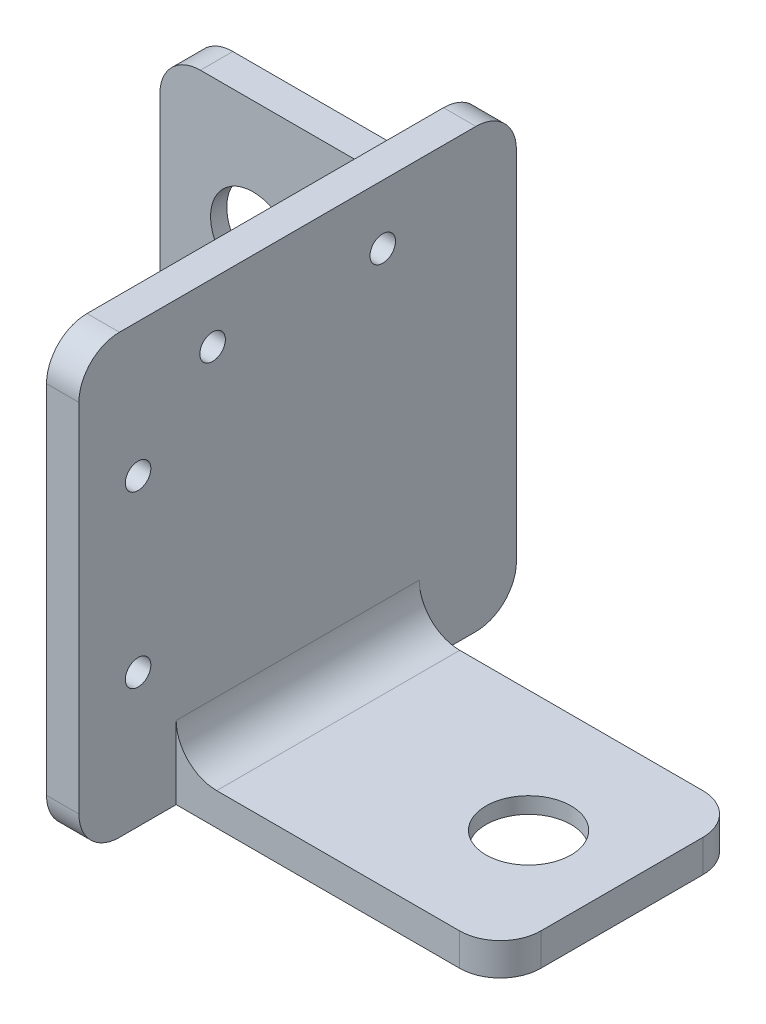
SolidWorks part; units mm, degrees
material "Du"
ref_plane "Front Plane" through (0, 0, 0) normal (0, 0, 1) x (1, 0, 0)
ref_plane "Top Plane" through (0, 0, 0) normal (0, 1, 0) x (1, 0, 0)
ref_plane "Right Plane" through (0, 0, 0) normal (1, 0, 0) x (0, 0, -1)
sketch "Sketch1" plane through (0, 0, 0) normal (1, 0, 0) x (0, 0, -1)
  line L1 (-27, -27) -> (27, -27)
  line L2 (-27, -27) -> (-27, 27)
  line L3 (-27, 27) -> (27, 27)
  line L4 (27, -27) -> (27, 27)
  line L5 (-27, -27) -> (27, 27) construction
  line L6 (-27, 27) -> (27, -27) construction
  point P0 (0, 0)
  dimension "D1" = 54
  dimension "D2" = 54
extrude "Boss-Extrude1" add sketch "Sketch1" along normal blind 4
fillet "Fillet1" radius 5 4 edges at (2, -27, 27) (2, -27, -27) (2, 27, -27) (2, 27, 27)
sketch "Sketch2" plane through (4, 0, 0) normal (1, 0, 0) x (0, 0, -1)
  line L0 (-22, -27) -> (22, -27) construction
  line L1 (-14.9965, -27) -> (15.0035, -27)
  line L2 (-14.9965, -27) -> (-14.9965, -23)
  line L3 (-14.9965, -23) -> (15.0035, -23)
  line L4 (15.0035, -27) -> (15.0035, -23)
  dimension "D1" = 30
  dimension "D2" = 4
extrude "Boss-Extrude2" add sketch "Sketch2" along normal blind 3
sketch "Sketch3" plane through (7, 0, 0) normal (1, 0, 0) x (0, 0, -1)
  line L1 (-14.9965, -27) -> (15.0035, -27)
  line L2 (-14.9965, -27) -> (-14.9965, -23)
  line L3 (-14.9965, -23) -> (15.0035, -23)
  line L4 (15.0035, -27) -> (15.0035, -23)
  dimension "D1" = 30
  dimension "D2" = 4
extrude "Boss-Extrude3" add sketch "Sketch3" along normal blind 37
sketch "Sketch4" plane through (0, 0, 0) normal (-1, 0, 0) x (0, 0, 1)
  line L0 (-27, -22) -> (-27, 22) construction
  line L1 (-27, 15.0038) -> (-23, 15.0038)
  line L2 (-27, 15.0038) -> (-27, -14.9964)
  line L3 (-27, -14.9964) -> (-23, -14.9964)
  line L4 (-23, 15.0038) -> (-23, -14.9964)
  dimension "D1" = 30.0002
  dimension "D2" = 4
extrude "Boss-Extrude6" add sketch "Sketch4" along normal blind 3
sketch "Sketch6" plane through (-3, 0, 0) normal (-1, 0, 0) x (0, 0, 1)
  line L0 (-27, -14.9964) -> (-23, -14.9964) construction
  line L1 (-27, 15.0038) -> (-23, 15.0038)
  line L2 (-27, 15.0038) -> (-27, -14.9964)
  line L3 (-27, -14.9964) -> (-23, -14.9964)
  line L4 (-23, 15.0038) -> (-23, -14.9964)
  dimension "D1" = 30.0002
  dimension "D2" = 4
extrude "Boss-Extrude7" add sketch "Sketch6" along normal blind 33
fillet "Fillet2" radius 5 4 edges at (44, -25, -15.0035) (44, -25, 14.9965) (-36, 15.0038, -25) (-36, -14.9964, -25)
sketch "Sketch7" plane through (0, 0, -27) normal (0, 0, -1) x (-1, 0, 0)
  line L0 (2.2, 0) -> (-2.2, 0) construction
  line L1 (36, 10.0038) -> (36, -9.9964) construction
  circle A0 centre (24.5, 0) radius 1.25
  dimension "D1" = 2.5
  dimension "D2" = 11.5
extrude "Cut-Extrude1" cut sketch "Sketch7" against normal through all
sketch "Sketch8" plane through (0, -27, 0) normal (0, -1, 0) x (-1, 0, 0)
  line L0 (-2.2, 0) -> (2.2, 0) construction
  line L1 (-44, -9.9965) -> (-44, 10.0035) construction
  circle A0 centre (-32.5, 0) radius 1.25
  dimension "D1" = 2.5
  dimension "D2" = 11.5
extrude "Cut-Extrude2" cut sketch "Sketch8" against normal through all
sketch "Sketch9" plane through (4, 0, 0) normal (1, 0, 0) x (0, 0, -1)
  line L0 (22, 27) -> (-22, 27) construction
  line L1 (-27, 22) -> (-27, -22) construction
  circle A0 centre (-10.5, 19.7) radius 1.575
  dimension "D1" = 3.15
  dimension "D2" = 7.3
  dimension "D3" = 16.5
extrude "Cut-Extrude3" cut sketch "Sketch9" against normal through all
sketch "Sketch10" plane through (4, 0, 0) normal (1, 0, 0) x (0, 0, -1)
  line L0 (22, 27) -> (-22, 27) construction
  line L1 (27, -22) -> (27, 22) construction
  circle A0 centre (10.5, 19.7) radius 1.575
  dimension "D1" = 3.15
  dimension "D2" = 7.3
  dimension "D3" = 16.5
extrude "Cut-Extrude4" cut sketch "Sketch10" against normal through all
fillet "Fillet6" radius 5 1 edges at (4, -23, -0.0035)
sketch "Sketch11" plane through (0, 0, 0) normal (-1, 0, 0) x (0, 0, 1)
  line L0 (27, 22) -> (27, -22) construction
  line L1 (-22, 27) -> (22, 27) construction
  circle A0 centre (19.7, 10.5) radius 1.575
  dimension "D1" = 3.15
  dimension "D2" = 7.3
  dimension "D3" = 16.5
extrude "Cut-Extrude5" cut sketch "Sketch11" against normal through all
sketch "Sketch12" plane through (0, 0, 0) normal (-1, 0, 0) x (0, 0, 1)
  line L0 (27, 22) -> (27, -22) construction
  line L1 (22, -27) -> (-22, -27) construction
  circle A0 centre (19.7, -10.5) radius 1.575
  dimension "D1" = 3.15
  dimension "D2" = 7.3
  dimension "D3" = 16.5
extrude "Cut-Extrude6" cut sketch "Sketch12" against normal blind 33
sketch "Sketch14" plane through (0, -14.9964, 0) normal (0, -1, 0) x (-1, 0, 0)
  line L0 (0, 29.7) -> (0, -29.7) construction
  line L1 (31, 23) -> (0, 23) construction
  line L2 (16.7901, 24.7665) -> (-3.2465, 21.2335) construction
  line L3 (1.5661, 25.925) -> (-1.5661, 8.1611) construction
  line L4 (6.7718, 23) -> (0, 23)
  line L5 (0, 23) -> (0, 17.0431)
  spline S0 degree 3 poles (0, 17.0431) (0.522, 20.0037) (3.4323, 22.4112) (6.7718, 23) knots 0 0 0 0 1 1 1 1
  dimension "D1" = 10
  dimension "D2" = 10
extrude "Boss-Extrude10" add sketch "Sketch14" against normal blind 30
sketch "Sketch15" plane through (0, -27, 0) normal (0, -1, 0) x (-1, 0, 0)
  circle A0 centre (-32.5, 0) radius 11
  dimension "D1" = 22
extrude "Cut-Extrude7" cut sketch "Sketch15" against normal blind 2
sketch "Sketch16" plane through (0, -23, 0) normal (0, 1, 0) x (1, 0, 0)
  circle A0 centre (32.5, 0) radius 5.25
  dimension "D1" = 10.5
extrude "Cut-Extrude8" cut sketch "Sketch16" against normal blind 2
sketch "Sketch17" plane through (0, 0, -27) normal (0, 0, -1) x (-1, 0, 0)
  circle A0 centre (24.5, 0) radius 11
  dimension "D1" = 22
extrude "Cut-Extrude9" cut sketch "Sketch17" against normal blind 2
sketch "Sketch18" plane through (0, 0, -23) normal (0, 0, 1) x (1, 0, 0)
  circle A0 centre (-24.5, 0) radius 5.25
  dimension "D1" = 10.5
extrude "Cut-Extrude10" cut sketch "Sketch18" against normal blind 2
